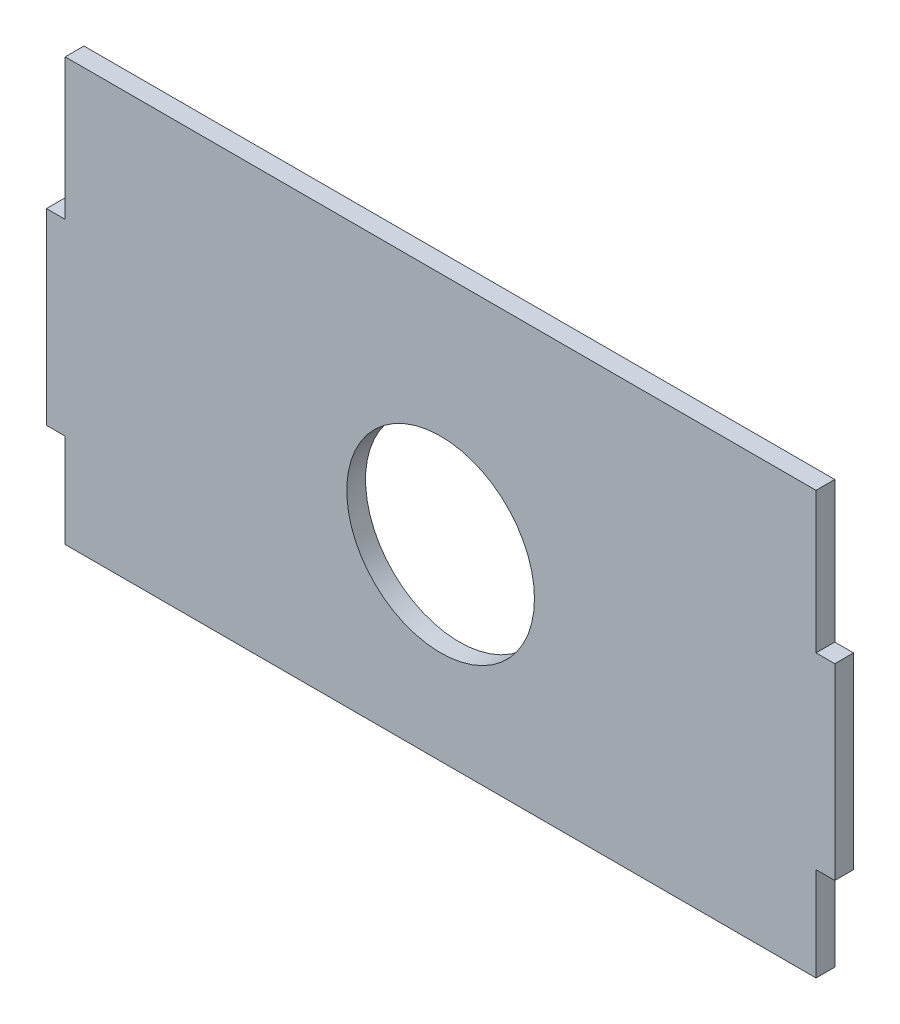
SolidWorks part; units mm, degrees
ref_plane "Спереди" through (0, 0, 0) normal (0, 0, 1) x (1, 0, 0)
ref_plane "Сверху" through (0, 0, 0) normal (0, 1, 0) x (1, 0, 0)
ref_plane "Справа" through (0, 0, 0) normal (1, 0, 0) x (0, 0, -1)
sketch "Эскиз1" plane through (0, 0, 0) normal (0, 0, 1) x (1, 0, 0)
  line L1 (0, 0) -> (80, 0)
  line L2 (0, 0) -> (0, 45)
  line L3 (0, 45) -> (80, 45)
  line L4 (80, 0) -> (80, 45)
  line L5 (80, 30) -> (82, 30)
  line L6 (80, 30) -> (80, 10)
  line L7 (80, 10) -> (82, 10)
  line L8 (82, 30) -> (82, 10)
  line L9 (0, 30) -> (-2, 30)
  line L10 (0, 30) -> (0, 10)
  line L11 (0, 10) -> (-2, 10)
  line L12 (-2, 30) -> (-2, 10)
  circle A0 centre (40, 20) radius 10
  point P14 (40, 45)
  point P15 (0, 22.5)
  dimension "D9" = 20
  dimension "D1" = 80
  dimension "D2" = 45
  dimension "D3" = 15
  dimension "D4" = 15
  dimension "D5" = 20
  dimension "D6" = 20
  dimension "D7" = 2
  dimension "D8" = 2
  dimension "D10" = 20
extrude "Бобышка-Вытянуть1" add sketch "Эскиз1" along normal blind 2 contours L8 L5 L4 L7 | L1 L4 L3 L2 | L12 L11 L10 L9
